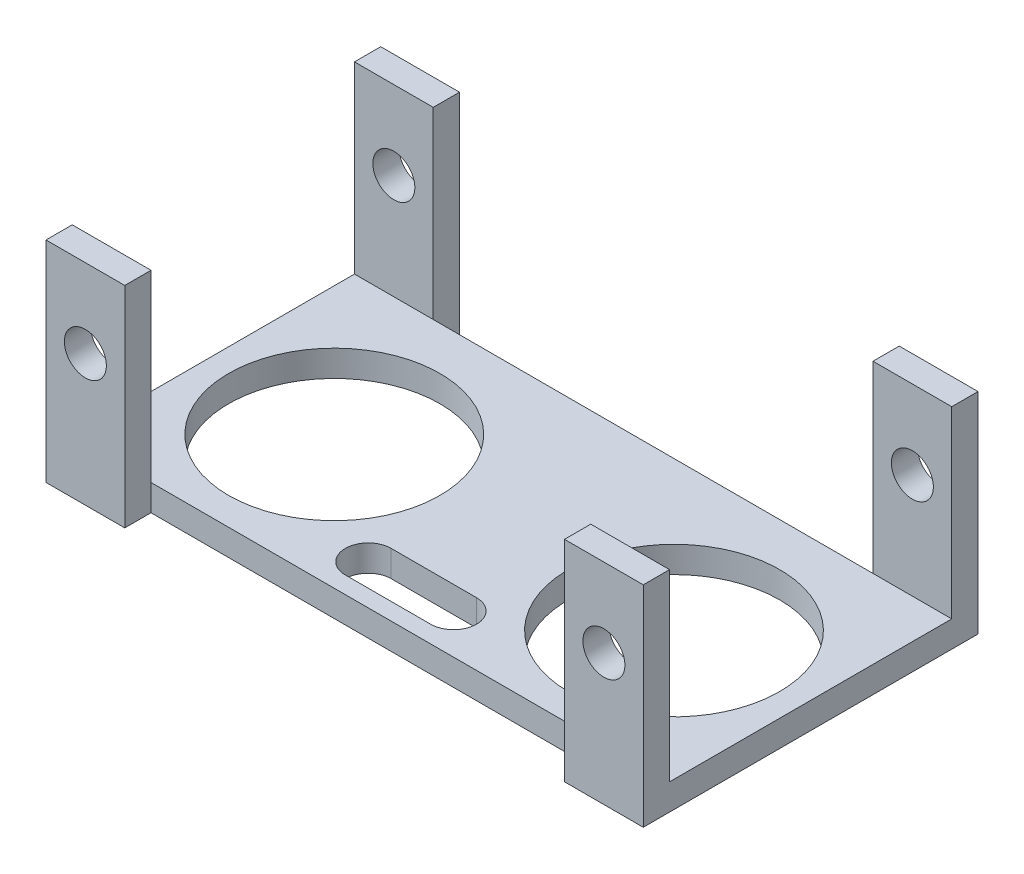
SolidWorks part; units mm, degrees
ref_plane "前基準面" through (0, 0, 0) normal (0, 0, 1) x (1, 0, 0)
ref_plane "上基準面" through (0, 0, 0) normal (0, 1, 0) x (1, 0, 0)
ref_plane "右基準面" through (0, 0, 0) normal (1, 0, 0) x (0, 0, -1)
sketch "草圖1" plane through (0, 0, 0) normal (0, 1, 0) x (1, 0, 0)
  line L1 (22.75, -10.75) -> (-22.75, -10.75)
  line L2 (22.75, -10.75) -> (22.75, 10.75)
  line L3 (22.75, 10.75) -> (-22.75, 10.75)
  line L4 (-22.75, -10.75) -> (-22.75, 10.75)
  line L5 (22.75, -10.75) -> (-22.75, 10.75) construction
  line L6 (22.75, 10.75) -> (-22.75, -10.75) construction
  point P0 (0, 0)
  dimension "D1" = 21.5
  dimension "D2" = 45.5
extrude "填料-伸長1" add sketch "草圖1" along normal blind 1
sketch "草圖2" plane through (0, 0, 10.75) normal (0, 0, 1) x (1, 0, 0)
  line L1 (-22.75, 0) -> (-16.75, 0)
  line L2 (-22.75, 0) -> (-22.75, 15)
  line L3 (-22.75, 15) -> (-16.75, 15)
  line L4 (-16.75, 0) -> (-16.75, 15)
  line L5 (0, 0) -> (0, 13.9724) construction
  line L6 (22.75, 0) -> (16.75, 0)
  line L7 (22.75, 0) -> (22.75, 15)
  line L8 (22.75, 15) -> (16.75, 15)
  line L9 (16.75, 0) -> (16.75, 15)
  line L10 (-22.75, 0) -> (22.75, 0) construction
  line L11 (-22.75, 1) -> (-22.75, 0) construction
  dimension "D1" = 15
  dimension "D2" = 6
extrude "填料-伸長2" add sketch "草圖2" along normal blind 2
mirror "鏡射1" about plane through (0, 0, 0) normal (0, 0, 1) of "填料-伸長2"
sketch "草圖3" plane through (0, 1, 0) normal (0, 1, 0) x (1, 0, 0)
  line L0 (0, 10.75) -> (0, -10.75) construction
  line L1 (16.75, 10.75) -> (-16.75, 10.75) construction
  line L2 (-16.75, -10.75) -> (16.75, -10.75) construction
  line L3 (-12.94, -0.6) -> (12.94, -0.6) construction
  circle A0 centre (-12.94, -0.6) radius 8.05
  circle A1 centre (12.94, -0.6) radius 8.05
  dimension "D2" = 16.1
  dimension "D1" = 25.88
  dimension "D3" = 10.15
extrude "除料-伸長1" cut sketch "草圖3" against normal through all
sketch "草圖4" plane through (0, 1, 0) normal (0, 1, 0) x (1, 0, 0)
  line L0 (-3.25, -7.7) -> (3.25, -7.7) construction
  line L4 (-3.25, -5.95) -> (3.25, -5.95)
  line L5 (-3.25, -9.45) -> (3.25, -9.45)
  line L6 (-16.75, -10.75) -> (16.75, -10.75) construction
  arc A2 (-3.25, -5.95) -> (-3.25, -9.45) centre (-3.25, -7.7) ccw
  arc A3 (3.25, -9.45) -> (3.25, -5.95) centre (3.25, -7.7) ccw
  point P2 (0, -7.7)
  dimension "D2" = 6.5
  dimension "D1" = 3.5
  dimension "D3" = 1.3
extrude "除料-伸長2" cut sketch "草圖4" against normal through all
sketch "草圖5" plane through (0, 0, -12.75) normal (0, 0, -1) x (-1, 0, 0)
  line L0 (-22.75, 15) -> (-16.75, 15) construction
  line L1 (16.75, 15) -> (22.75, 15) construction
  line L2 (-16.75, 0) -> (-22.75, 0) construction
  circle A0 centre (19.75, 9) radius 1.6
  circle A1 centre (-19.75, 9) radius 1.6
  point P7 (-19.75, 15)
  point P11 (19.75, 15)
  dimension "D1" = 3.2
  dimension "D2" = 9
extrude "除料-伸長3" cut sketch "草圖5" against normal through all
sketch "草圖6" plane through (0, 0, 0) normal (0, -1, 0) x (1, 0, 0)
  line L0 (3.25, 5.95) -> (-3.25, 5.95) construction
  line L1 (3.25, 5.95) -> (-3.25, 5.95)
  line L2 (-3.25, 9.45) -> (3.25, 9.45) construction
  line L3 (-3.25, 9.45) -> (3.25, 9.45)
  line L12 (-22.75, 12.75) -> (-22.75, -12.75)
  line L13 (-22.75, -12.75) -> (-16.75, -12.75)
  line L14 (-16.75, -12.75) -> (-16.75, -10.75)
  line L15 (-16.75, -10.75) -> (16.75, -10.75)
  line L16 (16.75, -10.75) -> (16.75, -12.75)
  line L17 (16.75, -12.75) -> (22.75, -12.75)
  line L18 (22.75, -12.75) -> (22.75, 12.75)
  line L19 (22.75, 12.75) -> (16.75, 12.75)
  line L20 (16.75, 12.75) -> (16.75, 10.75)
  line L21 (16.75, 10.75) -> (-16.75, 10.75)
  line L22 (-16.75, 10.75) -> (-16.75, 12.75)
  line L23 (-16.75, 12.75) -> (-22.75, 12.75)
  line L24 (-22.75, 12.75) -> (-22.75, -12.75)
  line L25 (-22.75, -12.75) -> (-16.75, -12.75)
  line L26 (-16.75, -12.75) -> (-16.75, -10.75)
  line L27 (-16.75, -10.75) -> (16.75, -10.75)
  line L28 (16.75, -10.75) -> (16.75, -12.75)
  line L29 (16.75, -12.75) -> (22.75, -12.75)
  line L30 (22.75, -12.75) -> (22.75, 12.75)
  line L31 (22.75, 12.75) -> (16.75, 12.75)
  line L32 (16.75, 12.75) -> (16.75, 10.75)
  line L33 (16.75, 10.75) -> (-16.75, 10.75)
  line L34 (-16.75, 10.75) -> (-16.75, 12.75)
  line L35 (-16.75, 12.75) -> (-22.75, 12.75)
  circle A0 centre (-12.94, 0.6) radius 8.05 construction
  circle A1 centre (-12.94, 0.6) radius 8.05
  arc A2 (-3.25, 9.45) -> (-3.25, 5.95) centre (-3.25, 7.7) ccw construction
  arc A3 (-3.25, 9.45) -> (-3.25, 5.95) centre (-3.25, 7.7) ccw
  arc A4 (3.25, 5.95) -> (3.25, 9.45) centre (3.25, 7.7) ccw construction
  arc A5 (3.25, 5.95) -> (3.25, 9.45) centre (3.25, 7.7) ccw
  circle A6 centre (12.94, 0.6) radius 8.05 construction
  circle A7 centre (12.94, 0.6) radius 8.05
  dimension "D1" = 0
extrude "填料-伸長3" add sketch "草圖6" along normal blind 1
